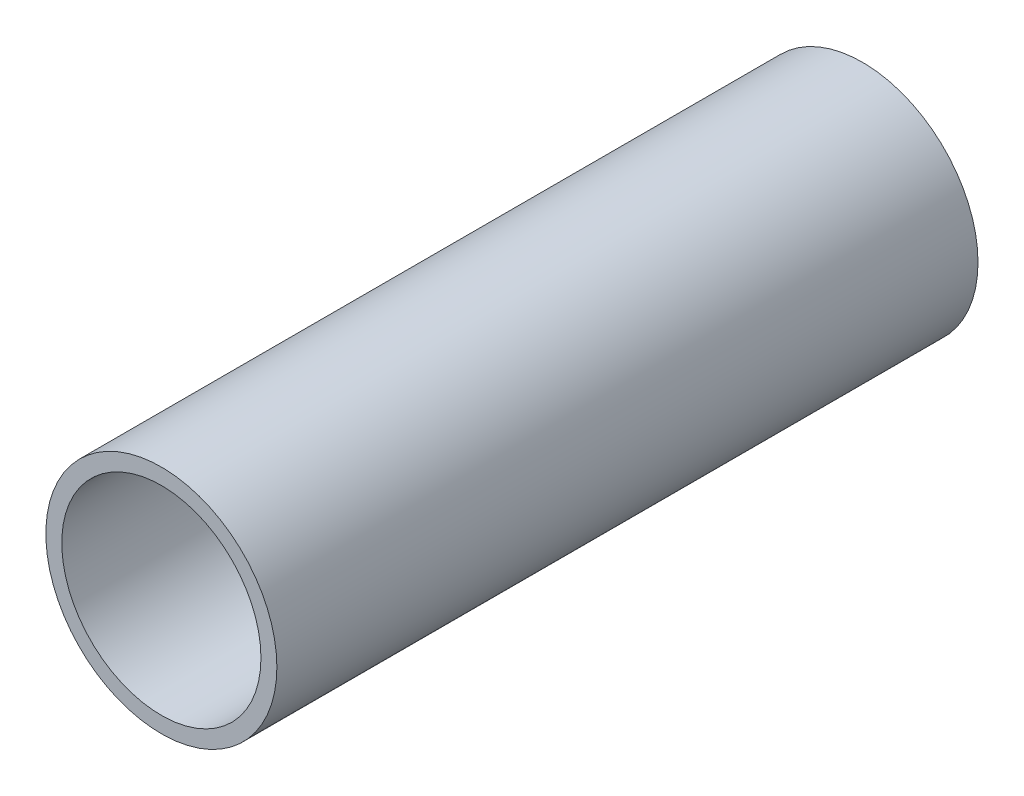
SolidWorks part; units mm, degrees
ref_plane "Front Plane" through (0, 0, 0) normal (0, 0, 1) x (1, 0, 0)
ref_plane "Top Plane" through (0, 0, 0) normal (0, 1, 0) x (1, 0, 0)
ref_plane "Right Plane" through (0, 0, 0) normal (1, 0, 0) x (0, 0, -1)
sketch "Sketch1" plane through (0, 0, 0) normal (0, 0, 1) x (1, 0, 0)
  circle A0 centre (0, 0) radius 12.5
  circle A1 centre (0, 0) radius 14.5
  dimension "D1" = 25
  dimension "D2" = 2
extrude "Boss-Extrude1" add sketch "Sketch1" along normal blind 88
